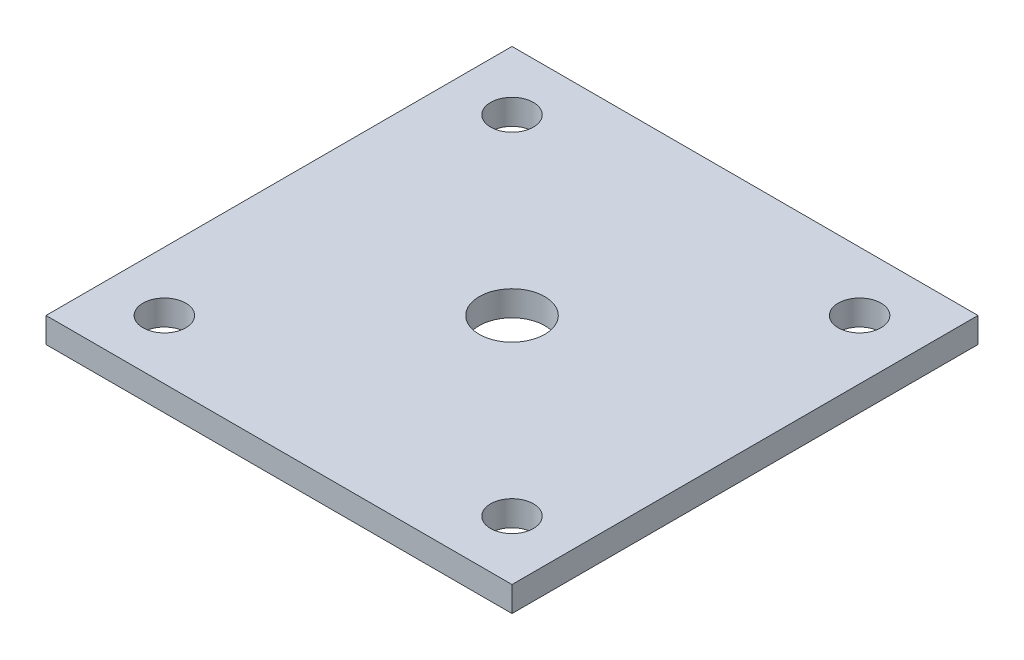
SolidWorks part; units mm, degrees
ref_plane "Front Plane" through (0, 0, 0) normal (0, 0, 1) x (1, 0, 0)
ref_plane "Top Plane" through (0, 0, 0) normal (0, 1, 0) x (1, 0, 0)
ref_plane "Right Plane" through (0, 0, 0) normal (1, 0, 0) x (0, 0, -1)
sketch "Sketch1" plane through (0, 0, 0) normal (0, 1, 0) x (1, 0, 0)
  line L0 (-17.526, 17.526) -> (17.526, 17.526)
  line L1 (17.526, 17.526) -> (17.526, -17.526)
  line L2 (17.526, -17.526) -> (-17.526, -17.526)
  line L3 (-17.526, -17.526) -> (-17.526, 17.526)
  line L5 (-23.495, -23.495) -> (23.495, -23.495)
  line L6 (-23.495, -23.495) -> (-23.495, 23.495)
  line L7 (-23.495, 23.495) -> (23.495, 23.495)
  line L8 (23.495, -23.495) -> (23.495, 23.495)
  line L9 (-23.495, -23.495) -> (23.495, 23.495) construction
  line L10 (-23.495, 23.495) -> (23.495, -23.495) construction
  circle A0 centre (-17.526, 17.526) radius 2.159
  circle A1 centre (17.526, 17.526) radius 2.159
  circle A2 centre (-17.526, -17.526) radius 2.159
  circle A3 centre (17.526, -17.526) radius 2.159
  circle A4 centre (0, 0) radius 3.302
  point P4 (0, 0)
  dimension "D2" = 4.318
  dimension "D5" = 6.604
  dimension "D1" = 46.99
  dimension "D3" = 35.052
  dimension "D4" = 35.052
extrude "Boss-Extrude1" add sketch "Sketch1" along normal blind 2.54 contours L5 L8 L7 L6 A3 L2 A2 L3 A0 L0 A1 L1 | A3 L1 A1 L0 A0 L3 A2 L2
